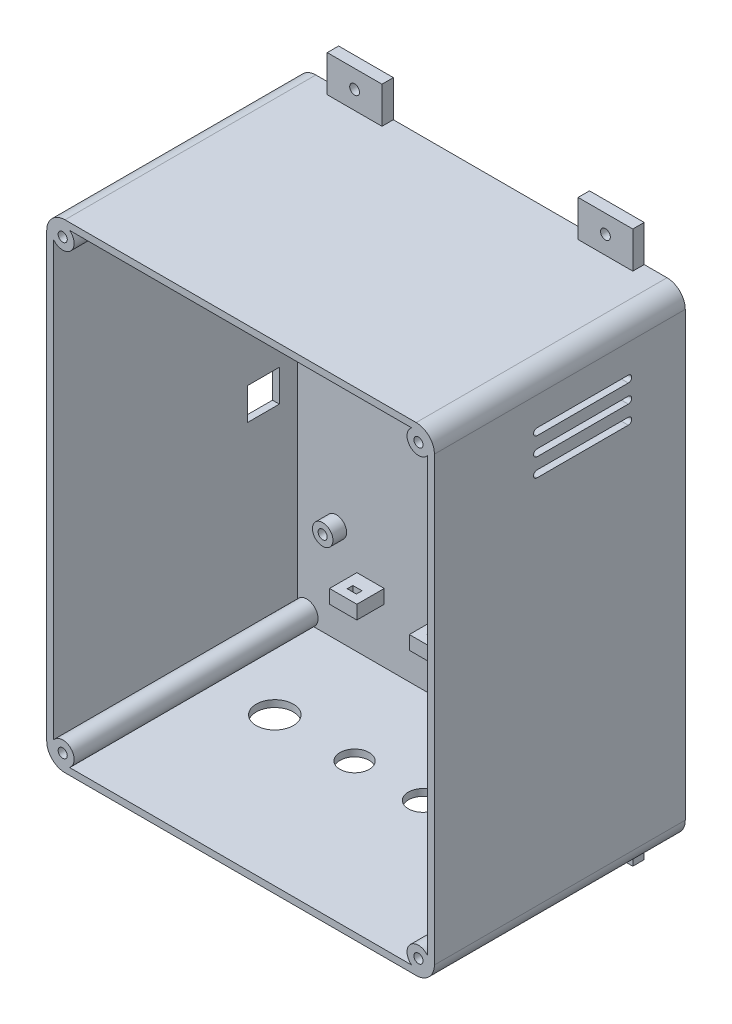
SolidWorks part; units mm, degrees
ref_plane "Front Plane" through (0, 0, 0) normal (0, 0, 1) x (1, 0, 0)
ref_plane "Top Plane" through (0, 0, 0) normal (0, 1, 0) x (1, 0, 0)
ref_plane "Right Plane" through (0, 0, 0) normal (1, 0, 0) x (0, 0, -1)
sketch "Sketch1" plane through (0, 0, 0) normal (0, 0, 1) x (1, 0, 0)
  line L0 (-77, 0) -> (77, 0)
  line L1 (85, 8) -> (85, 202)
  line L2 (77, 210) -> (-77, 210)
  line L3 (-85, 202) -> (-85, 8)
  arc A0 (-85, 8) -> (-77, 0) centre (-77, 8) ccw
  arc A1 (77, 0) -> (85, 8) centre (77, 8) ccw
  arc A2 (85, 202) -> (77, 210) centre (77, 202) ccw
  arc A3 (-77, 210) -> (-85, 202) centre (-77, 202) ccw
extrude "Block" add sketch "Sketch1" along normal blind 110
shell "Shell1" thickness 3
sketch "Sketch2" plane through (0, 0, 0) normal (0, 0, 1) x (1, 0, 0)
  circle A0 centre (-78, 7) radius 5
  circle A1 centre (78, 7) radius 5
  circle A2 centre (-78, 203) radius 5
  circle A3 centre (78, 203) radius 5
extrude "Corner columns" add sketch "Sketch2" along normal blind 110
ref_plane "P1_Front_110" through (0, 0, 110) normal (0, 0, 1) x (1, 0, 0)
sketch "Sketch3" plane through (0, 0, 110) normal (0, 0, 1) x (1, 0, 0)
  circle A0 centre (-78, 7) radius 2
  circle A1 centre (78, 7) radius 2
  circle A2 centre (-78, 203) radius 2
  circle A3 centre (78, 203) radius 2
extrude "Front panel insert holes" cut sketch "Sketch3" against normal blind 7
ref_plane "P2_Front_3" through (0, 0, 3) normal (0, 0, 1) x (1, 0, 0)
sketch "Sketch4" plane through (0, 0, 3) normal (0, 0, 1) x (1, 0, 0)
  circle A0 centre (-65, 46) radius 4.5
  circle A1 centre (65, 46) radius 4.5
  circle A2 centre (-65, 190) radius 4.5
  circle A3 centre (65, 190) radius 4.5
extrude "Plate bosses" add sketch "Sketch4" along normal blind 6
ref_plane "P3_Front_9" through (0, 0, 9) normal (0, 0, 1) x (1, 0, 0)
sketch "Sketch5" plane through (0, 0, 9) normal (0, 0, 1) x (1, 0, 0)
  circle A0 centre (-65, 46) radius 2
  circle A1 centre (65, 46) radius 2
  circle A2 centre (-65, 190) radius 2
  circle A3 centre (65, 190) radius 2
extrude "Plate insert holes" cut sketch "Sketch5" against normal blind 7
sketch "Sketch6" plane through (0, 0, 0) normal (0, 1, 0) x (1, 0, 0)
  circle A0 centre (-50, -45) radius 8.15
  circle A1 centre (-15, -45) radius 6.4
  circle A2 centre (15, -45) radius 6.4
  circle A3 centre (50, -45) radius 6.4
extrude "Cable gland holes" cut sketch "Sketch6" along normal blind 4
sketch "Sketch7" plane through (0, 0, 3) normal (0, 0, 1) x (1, 0, 0)
  line L1 (-56, 27) -> (-44, 27)
  line L2 (-56, 27) -> (-56, 33)
  line L3 (-56, 33) -> (-44, 33)
  line L4 (-44, 27) -> (-44, 33)
  line L5 (-56, 27) -> (-44, 33) construction
  line L6 (-56, 33) -> (-44, 27) construction
  line L7 (-21, 27) -> (-9, 27)
  line L8 (-21, 27) -> (-21, 33)
  line L9 (-21, 33) -> (-9, 33)
  line L10 (-9, 27) -> (-9, 33)
  line L11 (-21, 27) -> (-9, 33) construction
  line L12 (-21, 33) -> (-9, 27) construction
  line L13 (9, 27) -> (21, 27)
  line L14 (9, 27) -> (9, 33)
  line L15 (9, 33) -> (21, 33)
  line L16 (21, 27) -> (21, 33)
  line L17 (9, 27) -> (21, 33) construction
  line L18 (9, 33) -> (21, 27) construction
  line L19 (44, 27) -> (56, 27)
  line L20 (44, 27) -> (44, 33)
  line L21 (44, 33) -> (56, 33)
  line L22 (56, 27) -> (56, 33)
  line L23 (44, 27) -> (56, 33) construction
  line L24 (44, 33) -> (56, 27) construction
  point P0 (-50, 30)
  point P5 (-15, 30)
  point P10 (15, 30)
  point P15 (50, 30)
extrude "Cable tie bars" add sketch "Sketch7" along normal blind 12
ref_plane "P4_Top_26.99" through (0, 26.99, 0) normal (0, 1, 0) x (1, 0, 0)
sketch "Sketch8" plane through (0, 26.99, 0) normal (0, 1, 0) x (1, 0, 0)
  line L1 (-52, -11.25) -> (-48, -11.25)
  line L2 (-52, -11.25) -> (-52, -8.75)
  line L3 (-52, -8.75) -> (-48, -8.75)
  line L4 (-48, -11.25) -> (-48, -8.75)
  line L5 (-52, -11.25) -> (-48, -8.75) construction
  line L6 (-52, -8.75) -> (-48, -11.25) construction
  line L7 (-17, -11.25) -> (-13, -11.25)
  line L8 (-17, -11.25) -> (-17, -8.75)
  line L9 (-17, -8.75) -> (-13, -8.75)
  line L10 (-13, -11.25) -> (-13, -8.75)
  line L11 (-17, -11.25) -> (-13, -8.75) construction
  line L12 (-17, -8.75) -> (-13, -11.25) construction
  line L13 (13, -11.25) -> (17, -11.25)
  line L14 (13, -11.25) -> (13, -8.75)
  line L15 (13, -8.75) -> (17, -8.75)
  line L16 (17, -11.25) -> (17, -8.75)
  line L17 (13, -11.25) -> (17, -8.75) construction
  line L18 (13, -8.75) -> (17, -11.25) construction
  line L19 (48, -11.25) -> (52, -11.25)
  line L20 (48, -11.25) -> (48, -8.75)
  line L21 (48, -8.75) -> (52, -8.75)
  line L22 (52, -11.25) -> (52, -8.75)
  line L23 (48, -11.25) -> (52, -8.75) construction
  line L24 (48, -8.75) -> (52, -11.25) construction
  point P0 (-50, -10)
  point P5 (-15, -10)
  point P10 (15, -10)
  point P15 (50, -10)
extrude "Cable tie slots" cut sketch "Sketch8" along normal blind 6.02
ref_plane "P5_Right_-85" through (-85, 0, 0) normal (1, 0, 0) x (0, 0, -1)
sketch "Sketch9" plane through (-85, 0, 0) normal (1, 0, 0) x (0, 0, -1)
  line L1 (-25, 88) -> (-11, 88)
  line L2 (-25, 88) -> (-25, 102)
  line L3 (-25, 102) -> (-11, 102)
  line L4 (-11, 88) -> (-11, 102)
  line L5 (-25, 88) -> (-11, 102) construction
  line L6 (-25, 102) -> (-11, 88) construction
  point P0 (-18, 95)
extrude "USB access" cut sketch "Sketch9" along normal blind 4
ref_plane "P6_Right_-85" through (-85, 0, 0) normal (1, 0, 0) x (0, 0, -1)
sketch "Sketch10" plane through (-85, 0, 0) normal (1, 0, 0) x (0, 0, -1)
  line L0 (-25, 172) -> (-65, 172) construction
  line L1 (-25, 170.5) -> (-65, 170.5)
  line L2 (-25, 173.5) -> (-65, 173.5)
  line L3 (-25, 180) -> (-65, 180) construction
  line L4 (-25, 178.5) -> (-65, 178.5)
  line L5 (-25, 181.5) -> (-65, 181.5)
  line L6 (-25, 188) -> (-65, 188) construction
  line L7 (-25, 186.5) -> (-65, 186.5)
  line L8 (-25, 189.5) -> (-65, 189.5)
  arc A0 (-25, 170.5) -> (-25, 173.5) centre (-25, 172) ccw
  arc A1 (-65, 173.5) -> (-65, 170.5) centre (-65, 172) ccw
  arc A2 (-25, 178.5) -> (-25, 181.5) centre (-25, 180) ccw
  arc A3 (-65, 181.5) -> (-65, 178.5) centre (-65, 180) ccw
  arc A4 (-25, 186.5) -> (-25, 189.5) centre (-25, 188) ccw
  arc A5 (-65, 189.5) -> (-65, 186.5) centre (-65, 188) ccw
  point P2 (-45, 172)
  point P7 (-45, 180)
  point P14 (-45, 188)
  point P21 (0, 0)
extrude "Vents left" cut sketch "Sketch10" along normal blind 4
ref_plane "P7_Right_85" through (85, 0, 0) normal (1, 0, 0) x (0, 0, -1)
sketch "Sketch11" plane through (85, 0, 0) normal (1, 0, 0) x (0, 0, -1)
  line L0 (-25, 172) -> (-65, 172) construction
  line L1 (-25, 170.5) -> (-65, 170.5)
  line L2 (-25, 173.5) -> (-65, 173.5)
  line L3 (-25, 180) -> (-65, 180) construction
  line L4 (-25, 178.5) -> (-65, 178.5)
  line L5 (-25, 181.5) -> (-65, 181.5)
  line L6 (-25, 188) -> (-65, 188) construction
  line L7 (-25, 186.5) -> (-65, 186.5)
  line L8 (-25, 189.5) -> (-65, 189.5)
  arc A0 (-25, 170.5) -> (-25, 173.5) centre (-25, 172) ccw
  arc A1 (-65, 173.5) -> (-65, 170.5) centre (-65, 172) ccw
  arc A2 (-25, 178.5) -> (-25, 181.5) centre (-25, 180) ccw
  arc A3 (-65, 181.5) -> (-65, 178.5) centre (-65, 180) ccw
  arc A4 (-25, 186.5) -> (-25, 189.5) centre (-25, 188) ccw
  arc A5 (-65, 189.5) -> (-65, 186.5) centre (-65, 188) ccw
  point P2 (-45, 172)
  point P7 (-45, 180)
  point P14 (-45, 188)
  point P21 (0, 0)
extrude "Vents right" cut sketch "Sketch11" against normal blind 4
sketch "Sketch12" plane through (0, 0, 0) normal (0, 0, 1) x (1, 0, 0)
  circle A0 centre (-45, 165) radius 4.75
  circle A1 centre (45, 165) radius 4.75
extrude "Keyhole heads" cut sketch "Sketch12" along normal blind 4
sketch "Sketch13" plane through (0, 0, 0) normal (0, 0, 1) x (1, 0, 0)
  line L0 (-45, 165) -> (-45, 176) construction
  line L1 (-47.15, 165) -> (-47.15, 176)
  line L2 (-42.85, 165) -> (-42.85, 176)
  line L3 (45, 165) -> (45, 176) construction
  line L4 (42.85, 165) -> (42.85, 176)
  line L5 (47.15, 165) -> (47.15, 176)
  arc A0 (-47.15, 165) -> (-42.85, 165) centre (-45, 165) ccw
  arc A1 (-42.85, 176) -> (-47.15, 176) centre (-45, 176) ccw
  arc A2 (42.85, 165) -> (47.15, 165) centre (45, 165) ccw
  arc A3 (47.15, 176) -> (42.85, 176) centre (45, 176) ccw
  point P2 (-45, 170.5)
  point P7 (45, 170.5)
  point P14 (0, 0)
extrude "Keyhole slots" cut sketch "Sketch13" along normal blind 4
sketch "Sketch14" plane through (0, 0, 0) normal (0, 0, 1) x (1, 0, 0)
  line L1 (-67, -16) -> (-43, -16)
  line L2 (-67, -16) -> (-67, 0)
  line L3 (-67, 0) -> (-43, 0)
  line L4 (-43, -16) -> (-43, 0)
  line L6 (-67, 210) -> (-43, 210)
  line L7 (-67, 210) -> (-67, 226)
  line L8 (-67, 226) -> (-43, 226)
  line L9 (-43, 210) -> (-43, 226)
  line L11 (43, -16) -> (67, -16)
  line L12 (43, -16) -> (43, 0)
  line L13 (43, 0) -> (67, 0)
  line L14 (67, -16) -> (67, 0)
  line L16 (43, 210) -> (67, 210)
  line L17 (43, 210) -> (43, 226)
  line L18 (43, 226) -> (67, 226)
  line L19 (67, 210) -> (67, 226)
extrude "Wall ears" add sketch "Sketch14" along normal blind 5
sketch "Sketch15" plane through (0, 0, 0) normal (0, 0, 1) x (1, 0, 0)
  circle A0 centre (-55, -8) radius 2.15
  circle A1 centre (-55, 218) radius 2.15
  circle A2 centre (55, -8) radius 2.15
  circle A3 centre (55, 218) radius 2.15
extrude "Wall ear screw holes" cut sketch "Sketch15" along normal through all
